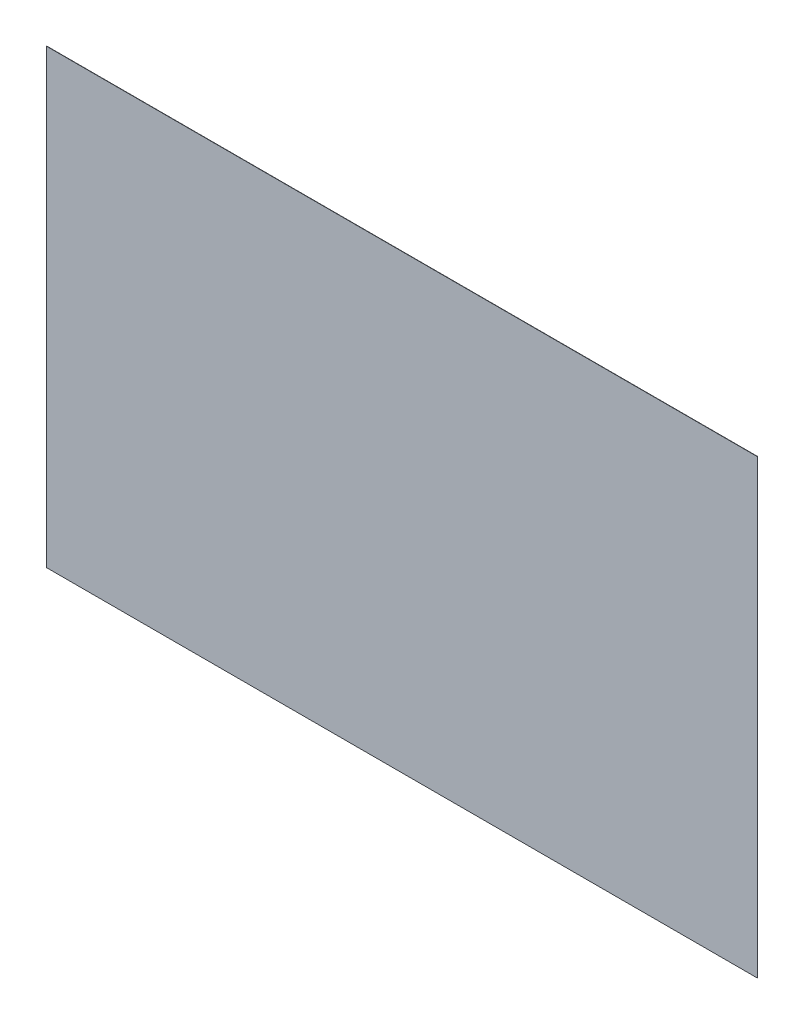
SolidWorks part; units mm, degrees
ref_plane "Front Plane" through (0, 0, 0) normal (0, 0, 1) x (1, 0, 0)
ref_plane "Top Plane" through (0, 0, 0) normal (0, 1, 0) x (1, 0, 0)
ref_plane "Right Plane" through (0, 0, 0) normal (1, 0, 0) x (0, 0, -1)
sketch "Sketch1" plane through (0, 0, 0) normal (0, 0, 1) x (1, 0, 0)
  line L1 (0, 0) -> (2440, 0)
  line L2 (0, 0) -> (0, 1550)
  line L3 (0, 1550) -> (2440, 1550)
  line L4 (2440, 0) -> (2440, 1550)
  dimension "D1" = 2440
  dimension "D2" = 1550
extrude "Boss-Extrude1" add sketch "Sketch1" along normal blind 1
